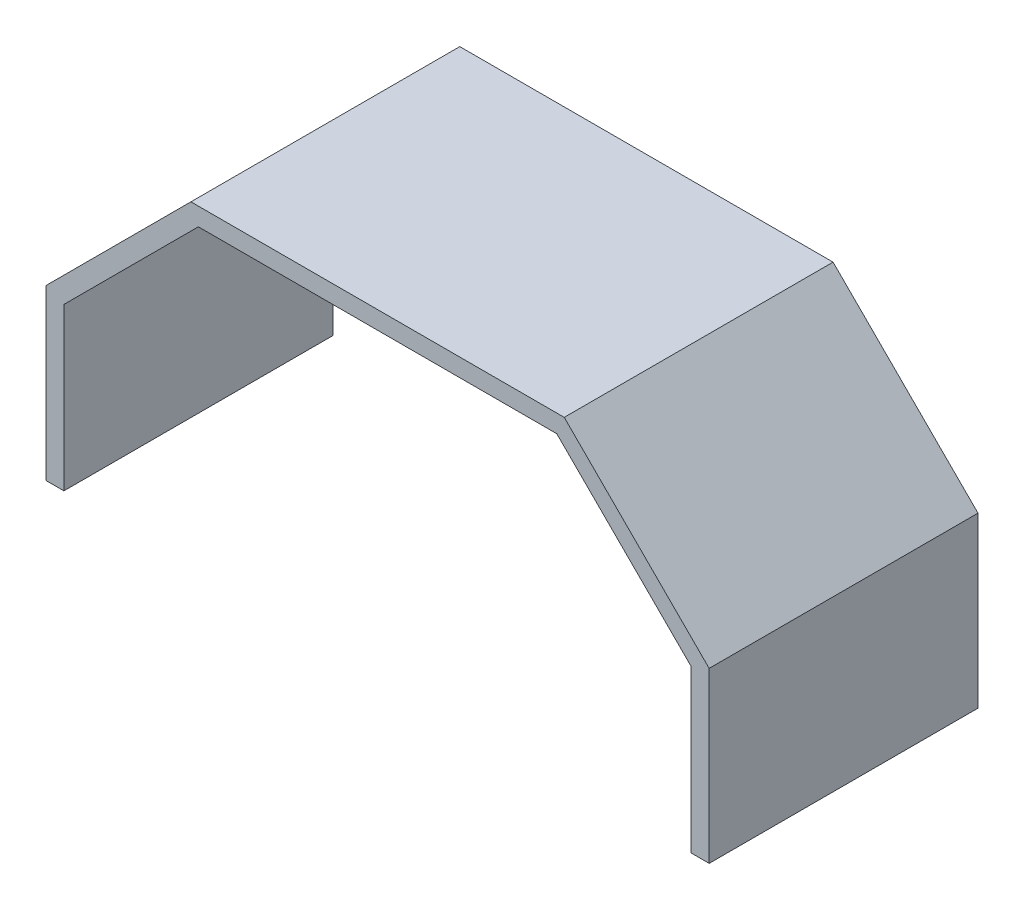
SolidWorks part; units mm, degrees
ref_plane "Front Plane" through (0, 0, 0) normal (0, 0, 1) x (1, 0, 0)
ref_plane "Top Plane" through (0, 0, 0) normal (0, 1, 0) x (1, 0, 0)
ref_plane "Right Plane" through (0, 0, 0) normal (1, 0, 0) x (0, 0, -1)
sketch "Sketch2" plane through (0, 0, 0) normal (0, 0, 1) x (1, 0, 0)
  line L0 (37, 13.5659) -> (35, 13.5659)
  line L1 (35, 31.5868) -> (35, 11.5868) construction
  line L2 (-37, 13.5659) -> (37, 13.5659) construction
  line L3 (35, 13.5659) -> (35, 31.5868)
  line L4 (35, 31.5868) -> (20, 46.5868)
  line L5 (20, 46.5868) -> (-20, 46.5868)
  line L6 (-20, 46.5868) -> (-35, 31.5868)
  line L7 (-35, 31.5868) -> (-35, 13.5659)
  line L8 (-35, 11.5868) -> (-35, 31.5868) construction
  line L9 (-35, 13.5659) -> (-37, 13.5659)
  line L10 (-37, 13.5659) -> (-37, 32.4152)
  line L11 (-37, 32.4152) -> (-20.8284, 48.5868)
  line L12 (-20.8284, 48.5868) -> (20.8284, 48.5868)
  line L13 (20.8284, 48.5868) -> (37, 32.4152)
  line L14 (37, 32.4152) -> (37, 13.5659)
extrude "Boss-Extrude1" add sketch "Sketch2" along normal blind 30
